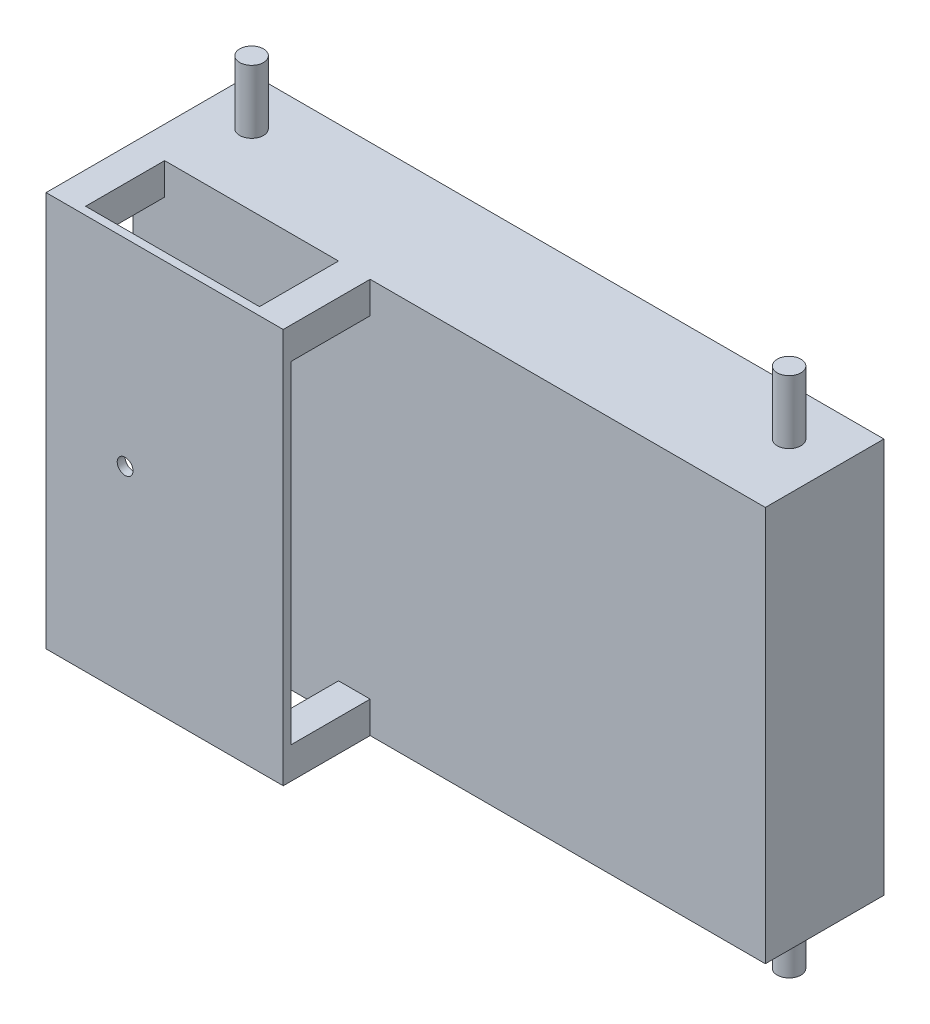
SolidWorks part; units mm, degrees
ref_plane "Front Plane" through (0, 0, 0) normal (0, 0, 1) x (1, 0, 0)
ref_plane "Top Plane" through (0, 0, 0) normal (0, 1, 0) x (1, 0, 0)
ref_plane "Right Plane" through (0, 0, 0) normal (1, 0, 0) x (0, 0, -1)
sketch "Sketch1" plane through (0, 0, 0) normal (0, 0, 1) x (1, 0, 0)
  line L1 (0, 0) -> (400, 0)
  line L2 (0, 0) -> (0, -250)
  line L3 (0, -250) -> (400, -250)
  line L4 (400, 0) -> (400, -250)
  dimension "D1" = 250
  dimension "D2" = 400
extrude "Boss-Extrude1" add sketch "Sketch1" along normal blind 5
sketch "Sketch2" plane through (0, 0, 5) normal (0, 0, 1) x (1, 0, 0)
  line L0 (150, 0) -> (150, -250)
  line L1 (400, 0) -> (0, 0) construction
  line L2 (0, -250) -> (400, -250) construction
  line L3 (0, 0) -> (0, -250) construction
  line L4 (148, -2) -> (148, -18)
  line L5 (0, 0) -> (20, 0)
  line L6 (0, 0) -> (0, -20)
  line L7 (0, -20) -> (20, -20)
  line L8 (20, 0) -> (20, -20)
  line L9 (150, 0) -> (130, 0)
  line L10 (150, 0) -> (150, -20)
  line L11 (150, -20) -> (130, -20)
  line L12 (130, 0) -> (130, -20)
  line L13 (0, -250) -> (20, -250)
  line L14 (0, -250) -> (0, -230)
  line L15 (0, -230) -> (20, -230)
  line L16 (20, -250) -> (20, -230)
  line L17 (150, -250) -> (130, -250)
  line L18 (150, -250) -> (150, -230)
  line L19 (150, -230) -> (130, -230)
  line L20 (130, -250) -> (130, -230)
  line L21 (148, -18) -> (132, -18)
  line L22 (132, -2) -> (132, -18)
  line L23 (148, -2) -> (132, -2)
  line L24 (2, -18) -> (18, -18)
  line L25 (18, -2) -> (18, -18)
  line L26 (2, -2) -> (18, -2)
  line L27 (2, -2) -> (2, -18)
  line L28 (2, -232) -> (18, -232)
  line L29 (18, -248) -> (18, -232)
  line L30 (2, -248) -> (18, -248)
  line L31 (2, -248) -> (2, -232)
  line L32 (148, -248) -> (148, -232)
  line L33 (148, -232) -> (132, -232)
  line L34 (132, -248) -> (132, -232)
  line L35 (148, -248) -> (132, -248)
  line M12 (0, 0) -> (0, -250)
  line M13 (0, -250) -> (400, -250)
  line M15 (400, 0) -> (0, 0)
  dimension "D1" = 150
  dimension "D2" = 20
  dimension "D3" = 20
  dimension "D4" = 20
  dimension "D5" = 20
  dimension "D6" = 20
  dimension "D7" = 20
  dimension "D8" = 20
  dimension "D9" = 20
  dimension "D10" = 2
  dimension "D11" = 2
extrude "Boss-Extrude3" add sketch "Sketch2" along normal blind 50 contours L16 L15 L30 L31 L28 L29 M13 M12 | L20 L0 L19 L32 L35 L34 L33 M13 | L8 L7 L27 L26 L25 L24 M15 M12 | L12 L11 L0 L23 L4 L21 L22 M15
sketch "Sketch3" plane through (0, 0, 55) normal (0, 0, 1) x (1, 0, 0)
  line L1 (0, 0) -> (150, 0)
  line L2 (0, 0) -> (0, -250)
  line L3 (0, -250) -> (150, -250)
  line L4 (150, 0) -> (150, -250)
extrude "Boss-Extrude4" add sketch "Sketch3" along normal blind 5
sketch "Sketch4" plane through (0, 0, 60) normal (0, 0, 1) x (1, 0, 0)
  line L0 (0, -250) -> (150, -250) construction
  line L1 (150, -250) -> (150, 0) construction
  circle A0 centre (50, -125) radius 5
  dimension "D1" = 125
  dimension "D2" = 100
extrude "Cut-Extrude1" cut sketch "Sketch4" against normal blind 5
sketch "Sketch5" plane through (0, 0, 0) normal (0, 0, -1) x (-1, 0, 0)
  line L0 (-5, -5) -> (-5, -245)
  line L1 (0, 0) -> (-400, 0)
  line L2 (0, 0) -> (0, -250)
  line L3 (0, -250) -> (-400, -250)
  line L4 (-400, 0) -> (-400, -250)
  line L5 (-5, -245) -> (-395, -245)
  line L6 (-395, -5) -> (-395, -245)
  line L7 (-5, -5) -> (-395, -5)
  dimension "D1" = 5
extrude "Boss-Extrude5" add sketch "Sketch5" along normal blind 70
sketch "Sketch6" plane through (0, 0, -70) normal (0, 0, -1) x (-1, 0, 0)
  line L1 (0, 0) -> (-400, 0)
  line L2 (0, 0) -> (0, -250)
  line L3 (0, -250) -> (-400, -250)
  line L4 (-400, 0) -> (-400, -250)
extrude "Boss-Extrude6" add sketch "Sketch6" against normal blind 5
sketch "Sketch7" plane through (0, -250, 0) normal (0, -1, 0) x (1, 0, 0)
  line L0 (0, 60) -> (0, -70) construction
  line L1 (400, 5) -> (400, -70) construction
  line L2 (400, -70) -> (0, -70) construction
  circle A0 centre (30, -40) radius 7.5
  circle A1 centre (370, -40) radius 7.5
  dimension "D1" = 15
  dimension "D2" = 15
  dimension "D3" = 30
  dimension "D4" = 30
  dimension "D5" = 30
  dimension "D6" = 30
extrude "Boss-Extrude7" add sketch "Sketch7" along normal blind 40
sketch "Sketch8" plane through (0, 0, 0) normal (0, 1, 0) x (1, 0, 0)
  line L0 (0, -60) -> (0, 70) construction
  line L1 (400, -5) -> (400, 70) construction
  line L2 (0, 70) -> (400, 70) construction
  circle A0 centre (370, 40) radius 7.5
  circle A1 centre (30, 40) radius 7.5
  dimension "D1" = 15
  dimension "D2" = 15
  dimension "D3" = 30
  dimension "D4" = 30
  dimension "D5" = 30
  dimension "D6" = 30
extrude "Boss-Extrude8" add sketch "Sketch8" along normal blind 40
